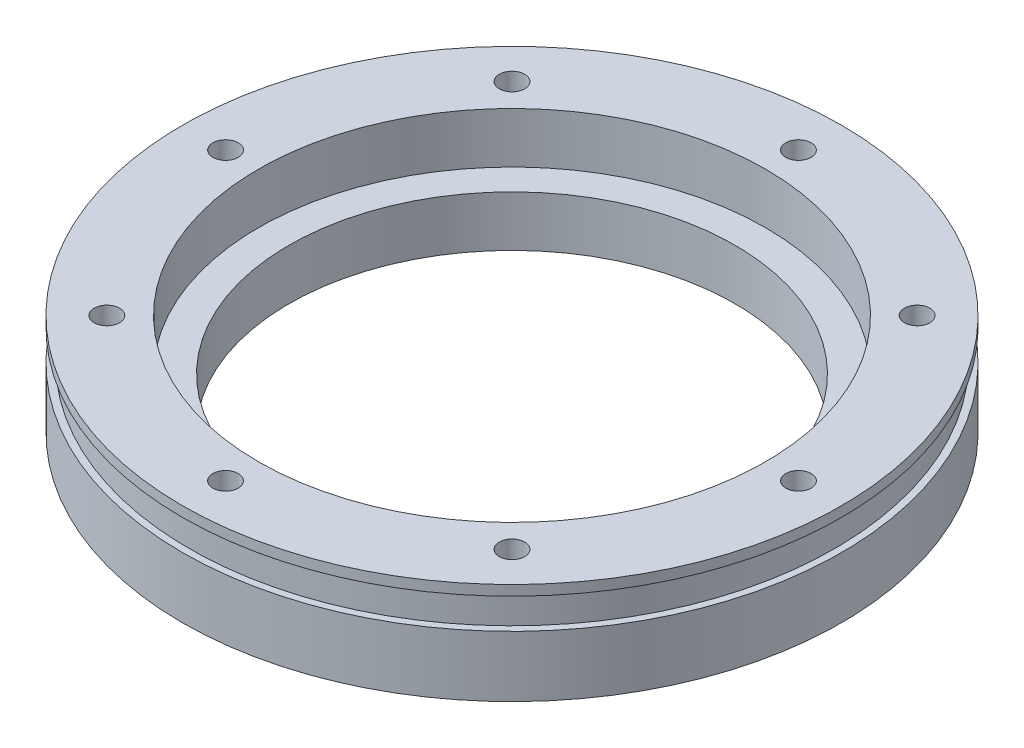
SolidWorks part; units mm, degrees
ref_plane "Front Plane" through (0, 0, 0) normal (0, 0, 1) x (1, 0, 0)
ref_plane "Top Plane" through (0, 0, 0) normal (0, 1, 0) x (1, 0, 0)
ref_plane "Right Plane" through (0, 0, 0) normal (1, 0, 0) x (0, 0, -1)
sketch "Sketch1" plane through (0, 0, 0) normal (0, 1, 0) x (1, 0, 0)
  circle A0 centre (0, 0) radius 63.66
  dimension "D1" = 127.32
extrude "Boss-Extrude1" add sketch "Sketch1" along normal blind 10
sketch "Sketch2" plane through (0, 10, 0) normal (0, 1, 0) x (1, 0, 0)
  circle A0 centre (0, 0) radius 65
  dimension "D1" = 130
extrude "Boss-Extrude2" add sketch "Sketch2" against normal blind 2
sketch "Sketch3" plane through (0, 0, 0) normal (0, -1, 0) x (1, 0, 0)
  circle A0 centre (0, 0) radius 65
  dimension "D1" = 130
extrude "Boss-Extrude3" add sketch "Sketch3" along normal blind 10 and the other way blind 2
sketch "Sketch4" plane through (0, 10, 0) normal (0, 1, 0) x (1, 0, 0)
  circle A0 centre (0, 0) radius 56.5 construction
  circle A1 centre (0, 56.5) radius 2.5
  circle A2 centre (39.9515, 39.9515) radius 2.5
  circle A3 centre (56.5, 0) radius 2.5
  circle A4 centre (39.9515, -39.9515) radius 2.5
  circle A5 centre (0, -56.5) radius 2.5
  circle A6 centre (-39.9515, -39.9515) radius 2.5
  circle A7 centre (-56.5, 0) radius 2.5
  circle A8 centre (-39.9515, 39.9515) radius 2.5
  circle A9 centre (0, 0) radius 44
  point P21 (0, 0)
  dimension "D1" = 113
  dimension "D2" = 5
  dimension "D4" = 88
  dimension "D3" = 8
extrude "Cut-Extrude1" cut sketch "Sketch4" against normal through all
sketch "Sketch5" plane through (0, 10, 0) normal (0, 1, 0) x (1, 0, 0)
  circle A0 centre (0, 0) radius 50
  dimension "D1" = 100
extrude "Cut-Extrude2" cut sketch "Sketch5" against normal blind 10
